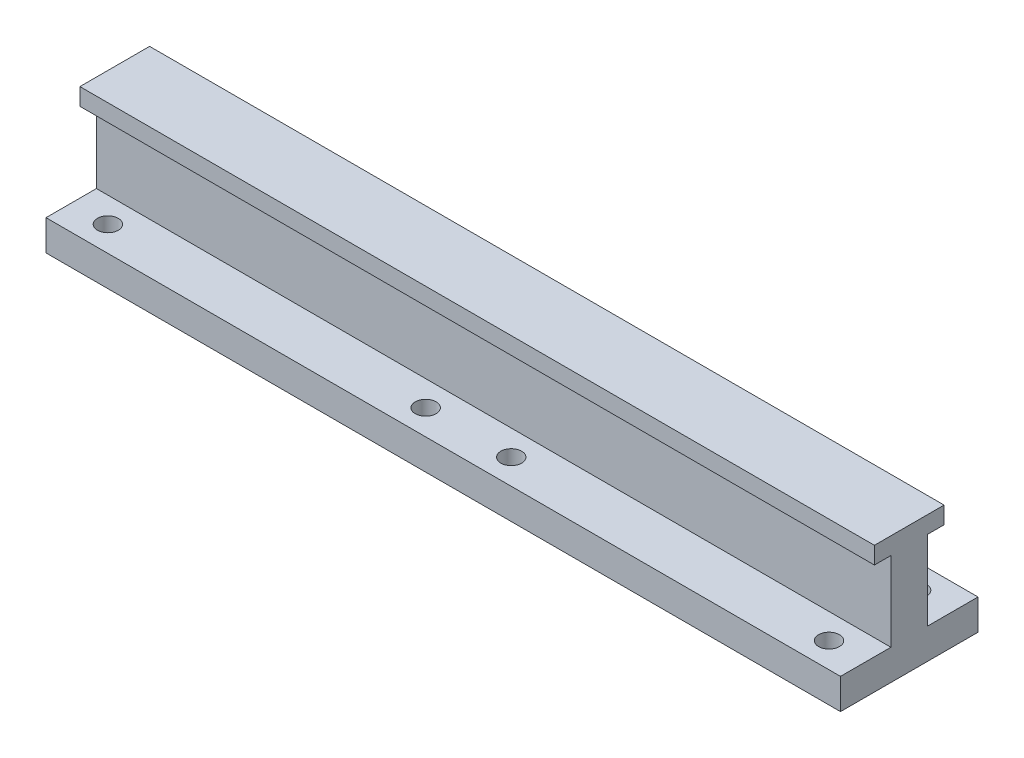
SolidWorks part; units mm, degrees
ref_plane "Front Plane" through (0, 0, 0) normal (0, 0, 1) x (1, 0, 0)
ref_plane "Top Plane" through (0, 0, 0) normal (0, 1, 0) x (1, 0, 0)
ref_plane "Right Plane" through (0, 0, 0) normal (1, 0, 0) x (0, 0, -1)
sketch "Sketch1" plane through (0, 0, 0) normal (0, 0, 1) x (1, 0, 0)
  line L1 (0, 0) -> (130, 0)
  line L2 (0, 0) -> (0, 5)
  line L3 (0, 5) -> (130, 5)
  line L4 (130, 0) -> (130, 5)
  dimension "D1" = 5
  dimension "D2" = 130
extrude "Boss-Extrude1" add sketch "Sketch1" along normal blind 22.5
sketch "Sketch3" plane through (0, 0, 0) normal (-1, 0, 0) x (0, 0, 1)
  line L0 (22.5, 5) -> (0, 5) construction
  line L1 (14.25, 5) -> (8.25, 5)
  line L2 (14.25, 5) -> (14.25, 15)
  line L3 (14.25, 15) -> (8.25, 15)
  line L4 (8.25, 5) -> (8.25, 15)
  line L5 (11.25, 5) -> (11.25, 25.0558) construction
  line L6 (8.25, 15) -> (14.25, 15)
  line L7 (8.25, 15) -> (8.25, 18)
  line L8 (8.25, 18) -> (14.25, 18)
  line L9 (14.25, 15) -> (14.25, 18)
  line L10 (5.55, 18) -> (16.95, 18)
  line L11 (5.55, 18) -> (5.55, 20.8)
  line L12 (5.55, 20.8) -> (16.95, 20.8)
  line L13 (16.95, 18) -> (16.95, 20.8)
  point P7 (11.25, 5)
  point P8 (11.25, 5)
  point P16 (11.25, 20.8)
  point P18 (11.25, 20.8)
  line M15 (22.5, 5) -> (0, 5)
  dimension "D1" = 6
  dimension "D2" = 10
  dimension "D3" = 3
  dimension "D4" = 11.4
  dimension "D5" = 2.8
extrude "Boss-Extrude2" add sketch "Sketch3" against normal up to surface (130 mm away) contours L5 L10 L13 L12 | L8 L5 L12 L11 L10 | L6 L5 L8 L7 | L5 L3 L9 L10 | L5 L2 L3 M15 | L1 L5 L6 L4 up to face at (130, 2.5, 11.25)
sketch "Sketch4" plane through (0, 5, 0) normal (0, 1, 0) x (1, 0, 0)
  line L1 (130, -8.25) -> (0, -8.25) construction
  line L2 (130, -14.25) -> (0, -14.25) construction
  line L3 (130, -14.25) -> (130, -8.25)
  line L4 (130, 0) -> (0, 0)
  line L5 (130, -22.5) -> (130, 0)
  line L6 (0, -22.5) -> (130, -22.5)
  line L7 (0, 0) -> (0, -22.5)
  line L8 (130, 0) -> (0, 0)
  line L9 (130, -22.5) -> (130, 0)
  line L10 (0, -22.5) -> (130, -22.5)
  line L11 (0, 0) -> (0, -22.5)
  line L12 (130, -8.25) -> (0, -8.25)
  line L13 (130, -14.25) -> (0, -14.25)
  line L14 (0, -22.5) -> (0, -14.25)
  line L15 (0, -18.375) -> (130, -18.375) construction
  line L16 (0, -11.25) -> (130, -11.25) construction
  circle A0 centre (6, -18.375) radius 1.7
  circle A3 centre (58, -18.375) radius 1.7
  circle A4 centre (72, -18.375) radius 1.7
  circle A5 centre (124, -18.375) radius 1.7
  circle A6 centre (124, -4.125) radius 1.7
  circle A7 centre (72, -4.125) radius 1.7
  circle A8 centre (58, -4.125) radius 1.7
  circle A9 centre (6, -4.125) radius 1.7
  dimension "D2" = 3.4
  dimension "D3" = 6
  dimension "D5" = 52
  dimension "D7" = 6
  dimension "D1" = 0
  dimension "D4" = 2
  dimension "D6" = 2
extrude "Cut-Extrude1" cut sketch "Sketch4" against normal up to next contours A0 | A3 | A4 | A5 | A6 | A7 | A8 | A9
